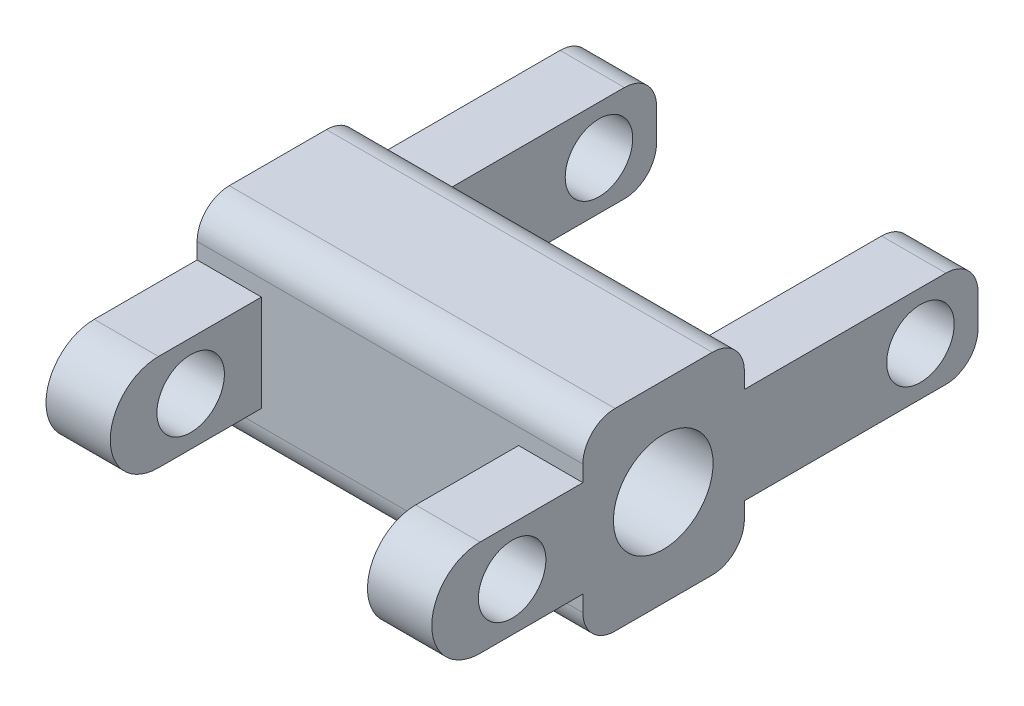
SolidWorks part; units mm, degrees
ref_plane "前视基准面" through (0, 0, 0) normal (0, 0, 1) x (1, 0, 0)
ref_plane "上视基准面" through (0, 0, 0) normal (0, 1, 0) x (1, 0, 0)
ref_plane "右视基准面" through (0, 0, 0) normal (1, 0, 0) x (0, 0, -1)
other "Configuration Table"
sketch "草图1" plane through (0, 0, 0) normal (0, 1, 0) x (1, 0, 0)
  line L0 (-6, 0) -> (6, 0)
  line L1 (-6, 0) -> (-6, -8.7)
  line L2 (-6, -8.7) -> (-4, -8.7)
  line L3 (-4, -8.7) -> (-4, -3)
  line L4 (-4, -3) -> (4, -3)
  line L5 (4, -3) -> (4, -8.7)
  line L6 (4, -8.7) -> (6, -8.7)
  line L7 (6, -8.7) -> (6, 0)
  point P4 (0, 0)
  dimension "D1" = 8.7
  dimension "D2" = 2
  dimension "D3" = 5.7
  dimension "D4" = 8
  dimension "D5" = 8.7
  dimension "D6" = 3
  dimension "D7" = 2
  dimension "D8" = 4
extrude "凸台-拉伸1" add sketch "草图1" along normal blind 3
sketch "草图2" plane through (-6, 0, 0) normal (-1, 0, 0) x (0, 0, 1)
  line L2 (6.2, 3) -> (0, 3)
  line L3 (0, 3) -> (0, 0)
  line L4 (0, 0) -> (6.2, 0)
  arc A0 (6.2, 0) -> (6.2, 3) centre (6.2, 1.5) ccw
  dimension "D2" = 3
  dimension "D1" = 1.5
  dimension "D3" = 6.2
extrude "切除-拉伸1" cut sketch "草图2" against normal blind 12 flip side to cut
sketch "草图3" plane through (-6, 0, 0) normal (-1, 0, 0) x (0, 0, 1)
  line L0 (6.2, 1.5) -> (5.2, 1.5) construction
  circle A2 centre (5.2, 1.5) radius 1.05
  dimension "D3" = 2.1
  dimension "D2" = 1
extrude "切除-拉伸2" cut sketch "草图3" against normal blind 12
sketch "草图4" plane through (0, 0, 0) normal (0, 0, -1) x (-1, 0, 0)
  line L0 (0, 3) -> (0, 0) construction
  line L1 (-6, 3) -> (6, 3) construction
  circle A0 centre (0, 1.5) radius 0.95
  dimension "D1" = 1.9
extrude "凸台-拉伸2" add sketch "草图4" along normal blind 4
ref_plane "基准面1" through (0, 0, -4) normal (0, 0, -1) x (-1, 0, 0)
sketch "草图5" plane through (0, 0, -4) normal (0, 0, -1) x (-1, 0, 0)
  line L1 (-5, 3) -> (-6, 3)
  line L3 (-6, 3) -> (-6, 0)
  line L15 (-5, 3) -> (5, 3)
  line L16 (-6, 3) -> (6, 3) construction
  line L18 (-6, 0) -> (6, 0) construction
  line L19 (4, 0) -> (-4, 0)
  line L21 (-6, 0) -> (-4, 0)
  line L22 (5, 3) -> (6, 3)
  line L23 (6, 3) -> (6, 0)
  line L24 (6, 0) -> (4, 0)
  line L25 (-6, 3) -> (-6, 0) construction
  line L26 (6, 3) -> (6, 0) construction
  point P5 (0, 3)
  dimension "D1" = 1
  dimension "D2" = 1
  dimension "D3" = 10
  dimension "D4" = 4
extrude "凸台-拉伸3" add sketch "草图5" along normal blind 8
sketch "草图6" plane through (6, 0, 0) normal (1, 0, 0) x (0, 0, -1)
  line L0 (12, 1.5) -> (7.5, 1.5) construction
  line L1 (12, 3) -> (12, 0) construction
  circle A1 centre (7.5, 1.5) radius 1.05
  dimension "D3" = 2.1
  dimension "D1" = 4.5
extrude "切除-拉伸3" cut sketch "草图6" against normal blind 12
sketch "草图8" plane through (0, 3, 0) normal (0, 1, 0) x (1, 0, 0)
  line L0 (-6, 12) -> (-4, 12) construction
  line L1 (-6, 12) -> (6, 12) construction
  line L2 (-4, 12) -> (4, 12)
  line L4 (-4, 5) -> (4, 5)
  line L8 (-4, 12) -> (-4, 5)
  line L9 (4, 12) -> (4, 5)
  line L10 (6, 12) -> (4, 12) construction
  line L11 (-6, 12) -> (6, 12) construction
  dimension "D1" = 2
  dimension "D2" = 2
  dimension "D3" = 5
extrude "切除-拉伸4" cut sketch "草图8" against normal blind 8
sketch "草图9" plane through (0, 3, 0) normal (0, 1, 0) x (1, 0, 0)
  line L1 (-3.5, 12) -> (-1.5, 12)
  line L7 (-1.5, 12) -> (-1.5, 9)
  line L9 (-1.5, 9) -> (-3.5, 9)
  line L11 (-3.5, 9) -> (-3.5, 12)
  dimension "D1" = 9
  dimension "D2" = 3
  dimension "D3" = 12
  dimension "D4" = 1.5
  dimension "D5" = 2
sketch "草图10" plane through (-6, 0, 0) normal (-1, 0, 0) x (0, 0, 1)
  line L0 (-12, 3) -> (-12, 5.5)
  line L2 (-8, 5.5) -> (-8, 3)
  line L4 (-8, 3) -> (-12, 3)
  arc A0 (-8, 5.5) -> (-12, 5.5) centre (-10, 5.5) ccw
  dimension "D2" = 2
  dimension "D1" = 2.5
  dimension "D3" = 3
  dimension "D4" = 5.5
  dimension "D5" = 10
  dimension "D6" = 2.5
extrude "凸台-拉伸5" add sketch "草图10" against normal blind 2
sketch "草图11" plane through (-6, 0, 0) normal (-1, 0, 0) x (0, 0, 1)
  circle A0 centre (-10, 5.5) radius 1.05
  dimension "D1" = 2.1
mirror "镜向1" about plane through (0, 0, 0) normal (1, 0, 0) of "凸台-拉伸5"
sketch "草图12" plane through (0, 0, -4) normal (0, 0, 1) x (1, 0, 0)
  line L0 (-4, 3) -> (-4, 0)
  line L1 (-4, 0) -> (4, 0)
  line L2 (4, 0) -> (4, 3)
  line L3 (4, 3) -> (-4, 3)
  dimension "D1" = 3
  dimension "D2" = 8
  dimension "D3" = 4
  dimension "D4" = 4
extrude "凸台-拉伸8" add sketch "草图12" along normal up to surface (4 mm away) up to face at (-0.95, 1.5, 0)
sketch "草图14" plane through (0, 0, 0) normal (0, 0, -1) x (-1, 0, 0)
  line L0 (-6, 3) -> (-6, 0)
  line L1 (-6, 0) -> (6, 0)
  line L2 (6, 0) -> (6, 3)
  line L3 (6, 3) -> (-6, 3)
extrude "凸台-拉伸9" add sketch "草图14" along normal blind 5
sketch "草图15" plane through (6, 0, 0) normal (1, 0, 0) x (0, 0, -1)
  line L0 (-5.2, 1.5) -> (-1.2, 1.5) construction
  circle A0 centre (-1.2, 1.5) radius 0.85
  dimension "D2" = 1.7
  dimension "D1" = 4
sketch "草图16" plane through (-6, 0, 0) normal (-1, 0, 0) x (0, 0, 1)
  line L0 (5.2, 1.5) -> (1.2, 1.5) construction
  circle A0 centre (1.2, 1.5) radius 0.6
  dimension "D1" = 1.2
extrude "切除-拉伸5" cut sketch "草图16" against normal blind 4
extrude "切除-拉伸6" cut sketch "草图15" against normal blind 4 contours A0
sketch "草图18" plane through (0, 3, 0) normal (0, 1, 0) x (1, 0, 0)
  line L1 (-6, 8) -> (-6, -6.2) construction
  line L2 (6, -6.2) -> (6, 8) construction
  line L4 (6, 2.0236) -> (-6, 2.0236)
  line L6 (-6, -3) -> (6, -3)
  line L7 (6, -5.2) -> (6, -1.2) construction
  line L8 (6, -3) -> (6, 2.0236)
  line L9 (-6, 2.0236) -> (-6, -3)
  dimension "D1" = 5.0236
  dimension "D2" = 2.0236
extrude "凸台-拉伸11" add sketch "草图18" against normal blind 6 from offset 1.5
sketch "草图19" plane through (6, 0, 0) normal (1, 0, 0) x (0, 0, -1)
  line L0 (-0.5, 1.5) -> (-5.2, 1.5) construction
  circle A0 centre (-0.5, 1.5) radius 1.55
  dimension "D1" = 3.1
  dimension "D2" = 0.5
extrude "切除-拉伸7" cut sketch "草图19" against normal through all
fillet "圆角1" radius 1 4 edges at (0, 4.5, -2.0236) (0, 4.5, 3) (0, -1.5, 3) (0, -1.5, -2.0236)
extrude "切除-拉伸8" cut sketch "草图11" against normal through all both contours A0
sketch "草图20" plane through (6, 0, 0) normal (1, 0, 0) x (0, 0, -1)
  line L0 (8, 3) -> (9.2902, 3)
  line L1 (9, 3) -> (12, 3) construction
  line L2 (9.2902, 3) -> (9.2902, 0)
  line L3 (2.0236, 0) -> (12, 0) construction
  line L4 (9.2902, 0) -> (12, 0)
  line L5 (12, 0) -> (12, 7.8863)
  line L6 (12, 7.8863) -> (8, 7.8863)
  line L7 (8, 7.8863) -> (8, 3)
  dimension "D1" = 7.8863
  dimension "D2" = 2.7098
  dimension "D3" = 9.2902
extrude "切除-拉伸9" cut sketch "草图20" against normal through all
fillet "圆角2" radius 1 4 edges at (5, 0, -9.2902) (-5, 0, -9.2902) (5, 3, -9.2902) (-5, 3, -9.2902)
sketch "草图21" plane through (0, 3, 0) normal (0, 1, 0) x (1, 0, 0)
  line L1 (-4, 5) -> (4, 5)
  line L2 (-4, 5) -> (-4, 2.7783)
  line L3 (-4, 2.7783) -> (4, 2.7783)
  line L4 (4, 5) -> (4, 2.7783)
  dimension "D1" = 2.7783
extrude "切除-拉伸10" cut sketch "草图21" against normal through all
